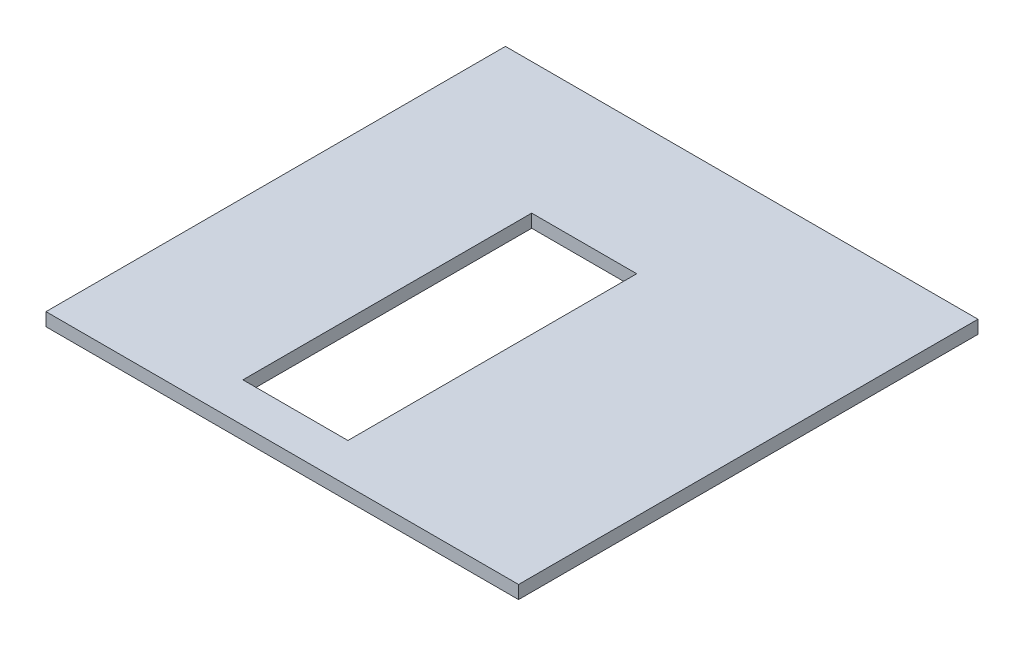
SolidWorks part; units mm, degrees
ref_plane "Front Plane" through (0, 0, 0) normal (0, 0, 1) x (1, 0, 0)
ref_plane "Top Plane" through (0, 0, 0) normal (0, 1, 0) x (1, 0, 0)
ref_plane "Right Plane" through (0, 0, 0) normal (1, 0, 0) x (0, 0, -1)
sketch "Sketch1" plane through (0, 0, 0) normal (0, 1, 0) x (1, 0, 0)
  line L1 (-180, 175) -> (180, 175)
  line L2 (-180, 175) -> (-180, -175)
  line L3 (-180, -175) -> (180, -175)
  line L4 (180, 175) -> (180, -175)
  line L5 (-180, 175) -> (180, -175) construction
  line L6 (-180, -175) -> (180, 175) construction
  line L7 (-60, 75) -> (20, 75)
  line L8 (-60, 75) -> (-60, -145)
  line L9 (-60, -145) -> (20, -145)
  line L10 (20, 75) -> (20, -145)
  line L11 (-60, 75) -> (20, -145) construction
  line L12 (-60, -145) -> (20, 75) construction
  point P0 (0, 0)
  point P6 (-20, -35)
  dimension "D1" = 350
  dimension "D2" = 360
  dimension "D3" = 80
  dimension "D4" = 220
  dimension "D5" = 160
  dimension "D6" = 100
extrude "Boss-Extrude1" add sketch "Sketch1" along normal blind 10
